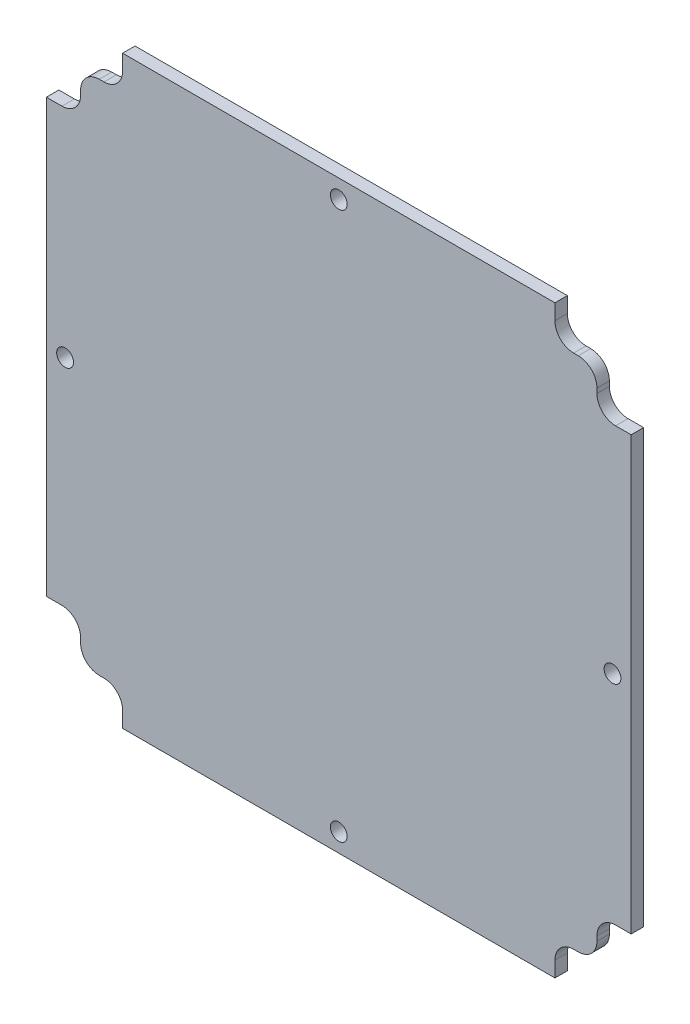
SolidWorks part; units mm, degrees
ref_plane "Front Plane" through (0, 0, 0) normal (0, 0, 1) x (1, 0, 0)
ref_plane "Top Plane" through (0, 0, 0) normal (0, 1, 0) x (1, 0, 0)
ref_plane "Right Plane" through (0, 0, 0) normal (1, 0, 0) x (0, 0, -1)
sketch "Sketch2" plane through (0, 0, 0) normal (0, 0, 1) x (1, 0, 0)
  line L0 (-5.8153, -2.0481) -> (-5.8153, 0.4519)
  line L1 (-2.8153, 3.4519) -> (-2.0653, 3.4519)
  line L2 (0.9347, 6.4519) -> (0.9347, 7.2019)
  line L3 (6.4347, 10.2019) -> (6.4347, 79.7019)
  line L4 (6.4347, 79.7019) -> (3.9347, 79.7019)
  line L5 (0.9347, 82.7019) -> (0.9347, 83.4519)
  line L6 (-2.0653, 86.4519) -> (-2.8153, 86.4519)
  line L7 (-5.8153, 89.4519) -> (-5.8153, 91.9519)
  line L8 (-5.8153, 91.9519) -> (-75.3153, 91.9519)
  line L9 (-75.3153, 91.9519) -> (-75.3153, 89.4519)
  line L10 (-78.3153, 86.4519) -> (-79.0653, 86.4519)
  line L11 (-82.0653, 83.4519) -> (-82.0653, 82.7019)
  line L12 (-85.0653, 79.7019) -> (-87.5653, 79.7019)
  line L13 (-87.5653, 79.7019) -> (-87.5653, 10.2019)
  line L14 (-87.5653, 10.2019) -> (-85.0653, 10.2019)
  line L15 (-82.0653, 7.2019) -> (-82.0653, 6.4519)
  line L16 (-79.0653, 3.4519) -> (-78.3153, 3.4519)
  line L17 (-75.3153, 0.4519) -> (-75.3153, -2.0481)
  line L18 (-75.3153, -2.0481) -> (-5.8153, -2.0481)
  line L19 (3.9347, 10.2019) -> (6.4347, 10.2019)
  arc A0 (0.9347, 7.2019) -> (3.9347, 10.2019) centre (3.9347, 7.2019) cw
  arc A1 (-2.0653, 3.4519) -> (0.9347, 6.4519) centre (-2.0653, 6.4519) ccw
  arc A2 (-5.8153, 0.4519) -> (-2.8153, 3.4519) centre (-2.8153, 0.4519) cw
  arc A3 (-78.3153, 3.4519) -> (-75.3153, 0.4519) centre (-78.3153, 0.4519) cw
  arc A4 (-82.0653, 6.4519) -> (-79.0653, 3.4519) centre (-79.0653, 6.4519) ccw
  arc A5 (-85.0653, 10.2019) -> (-82.0653, 7.2019) centre (-85.0653, 7.2019) cw
  arc A6 (3.9347, 79.7019) -> (0.9347, 82.7019) centre (3.9347, 82.7019) cw
  arc A7 (0.9347, 83.4519) -> (-2.0653, 86.4519) centre (-2.0653, 83.4519) ccw
  arc A8 (-2.8153, 86.4519) -> (-5.8153, 89.4519) centre (-2.8153, 89.4519) cw
  arc A9 (-79.0653, 86.4519) -> (-82.0653, 83.4519) centre (-79.0653, 83.4519) ccw
  arc A10 (-75.3153, 89.4519) -> (-78.3153, 86.4519) centre (-78.3153, 89.4519) cw
  arc A11 (-82.0653, 82.7019) -> (-85.0653, 79.7019) centre (-85.0653, 82.7019) cw
  circle A12 centre (-40.5653, 88.9519) radius 1.35
  circle A13 centre (-84.5653, 44.9519) radius 1.35
  circle A14 centre (3.4347, 44.9519) radius 1.35
  circle A15 centre (-40.5653, 0.9519) radius 1.35
  dimension "D1" = 3
  dimension "D6" = 2.7
  dimension "D5" = 0.75
  dimension "D2" = 12.25
  dimension "D3" = 94
  dimension "D4" = 69.5
  dimension "D7" = 3
  dimension "D8" = 47
  dimension "D9" = 3
  dimension "D10" = 47
  dimension "D12" = 47
  dimension "D14" = 3
  dimension "D16" = 47
  dimension "D17" = 3
extrude "Boss-Extrude1" add sketch "Sketch2" along normal blind 2
